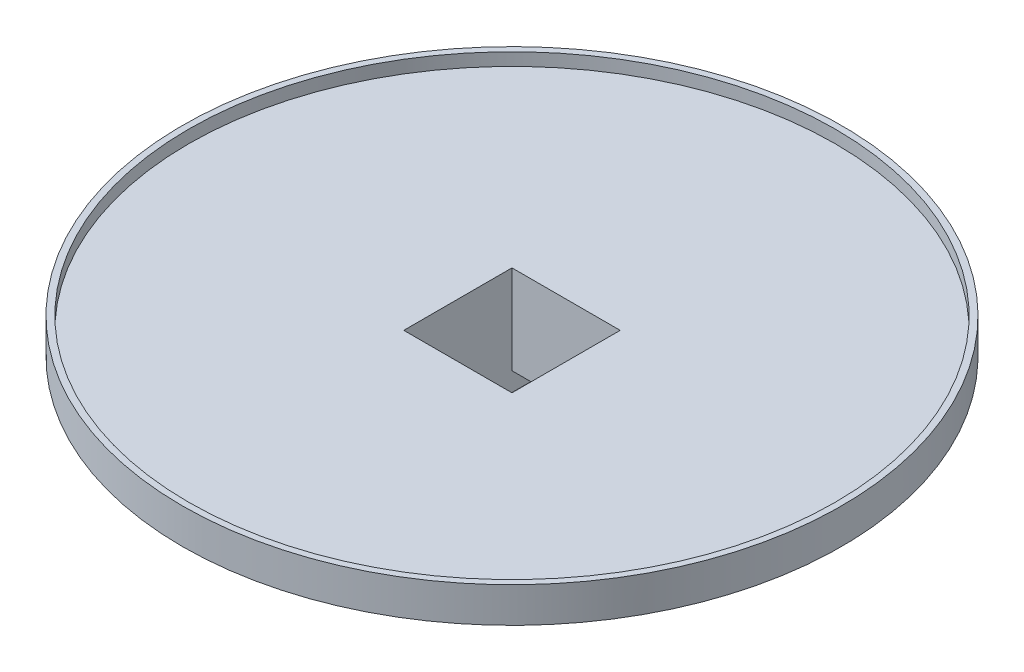
SolidWorks part; units mm, degrees
ref_plane "Front Plane" through (0, 0, 0) normal (0, 0, 1) x (1, 0, 0)
ref_plane "Top Plane" through (0, 0, 0) normal (0, 1, 0) x (1, 0, 0)
ref_plane "Right Plane" through (0, 0, 0) normal (1, 0, 0) x (0, 0, -1)
sketch "Sketch7" plane through (0, 0, 0) normal (0, -1, 0) x (1, 0, 0)
  line L7 (-4.3, -4.3) -> (4.3, -4.3)
  line L8 (-4.3, -4.3) -> (-4.3, 4.3)
  line L9 (-4.3, 4.3) -> (4.3, 4.3)
  line L10 (4.3, -4.3) -> (4.3, 4.3)
  line L11 (-4.3, -4.3) -> (4.3, 4.3) construction
  line L12 (-4.3, 4.3) -> (4.3, -4.3) construction
  circle A0 centre (0, 0) radius 25.69
  point P0 (0, 0)
  point P5 (0, 0)
  dimension "D1" = 51.38
  dimension "D4" = 8.6
extrude "Lens Spacer" add sketch "Sketch7" along normal blind 7.08
sketch "Sketch5" plane through (0, -7.08, 0) normal (0, -1, 0) x (-1, 0, 0)
  line L0 (-1000, 0) -> (49000, 0) construction
  line L1 (-12.5, -9.9) -> (-4.3, -9.9)
  line L2 (-12.5, -9.9) -> (-12.5, 14.1)
  line L3 (-12.5, 14.1) -> (-4.3, 14.1)
  line L12 (12.5, -9.9) -> (12.5, 14.1)
  line L13 (0, 4.3) -> (0, -4.3) construction
  line L19 (4.3, -9.9) -> (12.5, -9.9)
  line L21 (4.3, 14.1) -> (4.3, -9.9)
  line L22 (4.3, 14.1) -> (12.5, 14.1)
  line L25 (-4.3, 14.1) -> (-4.3, -9.9)
  line L28 (-4.3, 4.3) -> (-4.3, -4.3) construction
  line L29 (4.3, -4.3) -> (4.3, 4.3) construction
  line L30 (4.3, 4.3) -> (-4.3, 4.3) construction
  line L31 (-4.3, -4.3) -> (4.3, -4.3) construction
  circle A2 centre (-10.75, 12.5) radius 1.125
  circle A3 centre (-10.75, -0.3) radius 1.125
  circle A6 centre (10.25, -0.3) radius 1.125
  circle A7 centre (10.25, 12.5) radius 1.125
  point P27 (0, 4.3)
  point P32 (0, -4.3)
  dimension "D5" = 1.75
  dimension "D6" = 2.25
  dimension "D1" = 25
  dimension "D2" = 14.1
  dimension "D3" = 24
  dimension "D4" = 1.6
  dimension "D8" = 12.5
  dimension "D9" = 21
  dimension "D10" = 0.3
  dimension "D7" = 2
extrude "Attachment Legs" add sketch "Sketch5" along normal blind 1.5 contours A2 | A3 | L3 L25 L1 L2 | L21 L19 L12 L22 | A7 | A6
sketch "Sketch8" plane through (0, 0, 0) normal (0, 1, 0) x (1, 0, 0)
  circle A0 centre (0, 0) radius 26.19
  circle A1 centre (0, 0) radius 25.69
  circle A2 centre (0, 0) radius 25.69
  dimension "D2" = 0.5
  dimension "D1" = 0
extrude "Lens Positioner" add sketch "Sketch8" along normal blind 1.01 and the other way up to surface
sketch "Sketch11" plane through (0, -8.58, 0) normal (0, -1, 0) x (1, 0, 0)
  line L1 (5.9, -8.1) -> (9.9, -8.1)
  line L2 (5.9, -8.1) -> (5.9, -11.1)
  line L3 (5.9, -11.1) -> (9.9, -11.1)
  line L4 (4.3, 9.9) -> (4.3, -14.1)
  line L5 (4.3, -14.1) -> (12.5, -14.1)
  line L6 (12.5, -14.1) -> (12.5, 9.9)
  line L7 (12.5, 9.9) -> (4.3, 9.9)
  line L8 (4.3, 9.9) -> (4.3, -14.1)
  line L9 (4.3, -14.1) -> (12.5, -14.1)
  line L10 (12.5, -14.1) -> (12.5, 9.9)
  line L11 (12.5, 9.9) -> (4.3, 9.9)
  line L12 (9.9, -8.1) -> (9.9, -11.1)
  line L13 (5.9, -8.1) -> (9.9, -11.1) construction
  line L14 (5.9, -11.1) -> (9.9, -8.1) construction
  point P2 (7.9, -9.6)
  dimension "D2" = 6.6
  dimension "D3" = 4
  dimension "D4" = 3
  dimension "D5" = 3
  dimension "D1" = 0
extrude "Node Hole" cut sketch "Sketch11" against normal blind 0.7 contours L2 L1 L12 L3
sketch "Sketch13" plane through (0, 0, 0) normal (0, 0, 1) x (1, 0, 0)
  line L1 (-26.19, 1.01) -> (-26.19, -7.08) construction
  line L2 (-4.3, -7.08) -> (-12.5, -7.08) construction
  line L3 (-7.7, -7.08) -> (-26.19, -7.08)
  line L4 (-26.19, -7.08) -> (-26.19, -1.79)
  line L5 (26.19, 1.01) -> (-26.19, 1.01) construction
  arc A3 (-7.7, -7.08) -> (-11.2653, -4.4019) centre (-13.7835, -11.4665) ccw
  arc A4 (-11.2653, -4.4019) -> (-26.19, -1.79) centre (-26.3742, -46.7896) ccw
  dimension "D3" = 45
  dimension "D4" = 7.5
  dimension "D1" = 2.8
  dimension "D2" = 3.4
revolve "Cut-Revolve1" cut sketch "Sketch13" angle 360 about axis through (0, -81.1565, 0) along (0, 1, 0)
